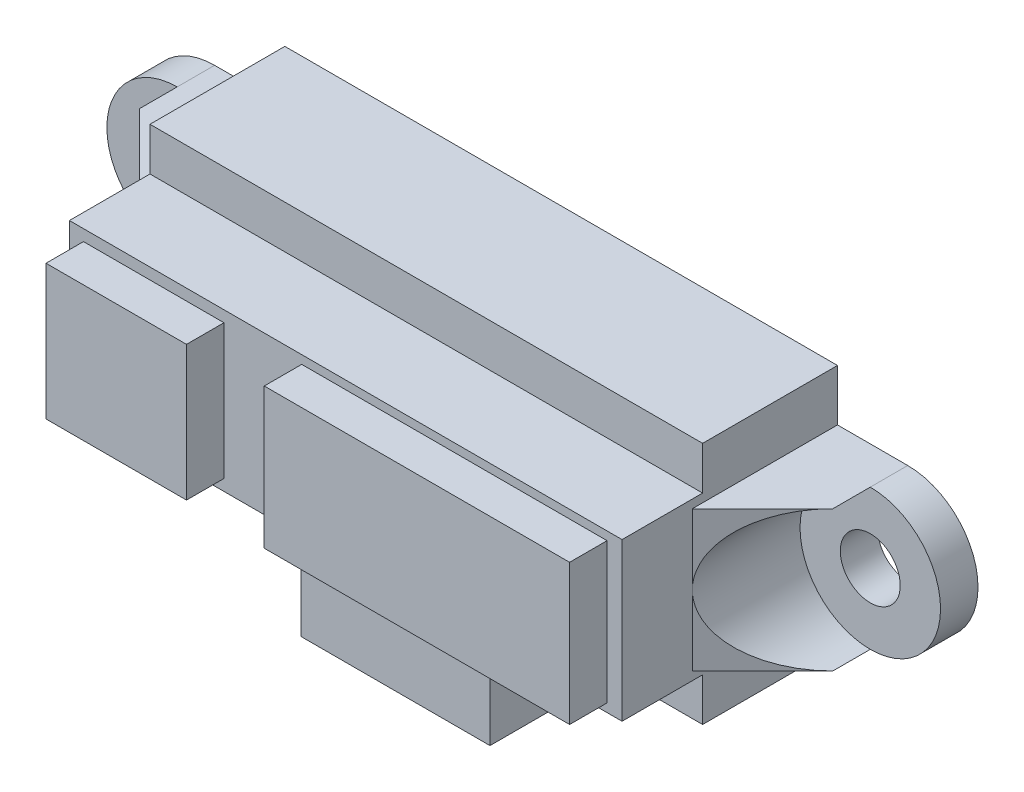
SolidWorks part; units mm, degrees
ref_plane "Front Plane" through (0, 0, 0) normal (0, 0, 1) x (1, 0, 0)
ref_plane "Top Plane" through (0, 0, 0) normal (0, 1, 0) x (1, 0, 0)
ref_plane "Right Plane" through (0, 0, 0) normal (1, 0, 0) x (0, 0, -1)
sketch "Sketch1" plane through (0, 0, 0) normal (0, 0, 1) x (1, 0, 0)
  line L1 (-14.75, 4.2) -> (14.75, 4.2)
  line L2 (-14.75, 4.2) -> (-14.75, -4.2)
  line L3 (-14.75, -4.2) -> (14.75, -4.2)
  line L4 (14.75, 4.2) -> (14.75, -4.2)
  line L5 (0, -4.2) -> (0, 4.2) construction
  line L6 (-14.75, 0) -> (14.75, 0) construction
  point P0 (0, 0)
  dimension "D1" = 29.5
  dimension "D2" = 8.4
extrude "Boss-Extrude1" add sketch "Sketch1" along normal blind 11.5
sketch "Sketch2" plane through (0, 0, 11.5) normal (0, 0, 1) x (1, 0, 0)
  line L0 (-14.75, 4.2) -> (-14.75, -4.2) construction
  line L1 (-14, 3.6) -> (-6.5, 3.6)
  line L2 (-14, 3.6) -> (-14, -3.6)
  line L3 (-14, -3.6) -> (-6.5, -3.6)
  line L4 (-6.5, 3.6) -> (-6.5, -3.6)
  line L5 (-10.25, -3.6) -> (-10.25, 3.6) construction
  line L6 (-14, 0) -> (-6.5, 0) construction
  line L8 (-2.35, 3.75) -> (13.95, 3.75)
  line L9 (-2.35, 3.75) -> (-2.35, -3.75)
  line L10 (-2.35, -3.75) -> (13.95, -3.75)
  line L11 (13.95, 3.75) -> (13.95, -3.75)
  line L12 (5.8, -3.75) -> (5.8, 3.75) construction
  line L13 (-2.35, 0) -> (13.95, 0) construction
  point P0 (-10.25, 0)
  point P6 (5.8, 0)
  dimension "D1" = 4.5
  dimension "D2" = 3.75
  dimension "D3" = 7.2
  dimension "D4" = 16.3
  dimension "D5" = 3.75
  dimension "4.15" = 4.15
extrude "Boss-Extrude2" add sketch "Sketch2" along normal blind 2
sketch "Sketch3" plane through (0, 0, 0) normal (0, 0, 1) x (1, 0, 0)
  line L0 (-14.75, 4.2) -> (-14.75, -4.2) construction
  line L1 (14.75, -6.5) -> (-14.75, -6.5)
  line L2 (14.75, -6.5) -> (14.75, 6.5)
  line L3 (14.75, 6.5) -> (-14.75, 6.5)
  line L4 (-14.75, -6.5) -> (-14.75, 6.5)
  line L5 (0, 6.5) -> (0, -6.5) construction
  line L6 (14.75, 0) -> (-14.75, 0) construction
  point P0 (0, 0)
  dimension "D1" = 13
extrude "Boss-Extrude3" add sketch "Sketch3" along normal offset from surface (7.2 mm away) 6.3 up to face at (-10.25, 0, 13.5)
sketch "Sketch4" plane through (0, 0, 0) normal (1, 0, 0) x (0, 0, -1)
  line L0 (-5.55, -6.5) -> (-5.55, -11.5)
  line L1 (-7.2, -6.5) -> (0, -6.5) construction
  line L2 (-5.55, -11.5) -> (-8.85, -11.5)
  line L3 (-8.85, -11.5) -> (-8.85, -6.5)
  line L4 (-8.85, -6.5) -> (-8.35, -6.5)
  line L5 (-8.35, -6.5) -> (-7.2, -5.35)
  line L6 (-7.2, -6.5) -> (-7.2, -4.2) construction
  line L7 (-7.2, -5.35) -> (-7.2, -6.5)
  line L8 (-7.2, -6.5) -> (-5.55, -6.5)
  dimension "D1" = 3.3
  dimension "D2" = 45
  dimension "D3" = 5
  dimension "D4" = 0.5
extrude "Boss-Extrude4" add sketch "Sketch4" along normal mid plane 10.1
sketch "Sketch5" plane through (0, 0, 0) normal (0, 0, 1) x (1, 0, 0)
  line L0 (-18.5, 3.75) -> (-14.75, 3.75)
  line L1 (-14.75, 4.2) -> (-14.75, -4.2) construction
  line L2 (-18.5, -3.75) -> (-14.75, -3.75)
  line L3 (-14.75, -3.75) -> (-14.75, 3.75)
  line L4 (18.5, 3.75) -> (14.75, 3.75)
  line L5 (14.75, -4.2) -> (14.75, 4.2) construction
  line L6 (18.5, -3.75) -> (14.75, -3.75)
  line L7 (14.75, -3.75) -> (14.75, 3.75)
  arc A0 (-18.5, 3.75) -> (-18.5, -3.75) centre (-18.5, 0) ccw
  arc A1 (18.5, -3.75) -> (18.5, 3.75) centre (18.5, 0) ccw
  circle A2 centre (-18.5, 0) radius 1.6
  circle A3 centre (18.5, 0) radius 1.6
  dimension "D1" = 3.75
  dimension "D2" = 3.2
  dimension "D3" = 37
extrude "Boss-Extrude5" add sketch "Sketch5" along normal blind 10
sketch "Sketch8" plane through (0, 0, 10) normal (0, 0, 1) x (1, 0, 0)
  circle A0 centre (-18.5, 0) radius 3.75
  arc A1 (-18.5, 3.75) -> (-18.5, -3.75) centre (-18.5, 0) ccw construction
  circle A2 centre (18.5, 0) radius 3.75
  arc A3 (18.5, -3.75) -> (18.5, 3.75) centre (18.5, 0) ccw construction
extrude "Cut-Extrude1" cut sketch "Sketch8" against normal offset from surface (8 mm away) 2 up to face at (0, 0, 0)
sketch "Sketch9" plane through (0, 0, 0) normal (0, 1, 0) x (1, 0, 0)
  line L0 (-18.5, -10) -> (-18.5, -2) construction
  line L1 (-18.5, -4) -> (-14.75, -7.75)
  line L2 (-14.75, -10) -> (-14.75, 0) construction
  line L3 (-14.75, -7.75) -> (-14.75, -10)
  line L4 (-14.75, -10) -> (-18.5, -10)
  line L5 (-18.5, -10) -> (-18.5, -4)
  line L6 (-22.25, -2) -> (-18.5, -2) construction
  line L7 (0, 0) -> (0, -16.9734) construction
  line L8 (18.5, -10) -> (18.5, -4)
  line L9 (14.75, -10) -> (18.5, -10)
  line L10 (14.75, -7.75) -> (14.75, -10)
  line L11 (18.5, -4) -> (14.75, -7.75)
  dimension "D1" = 45
  dimension "D2" = 2
extrude "Cut-Extrude2" cut sketch "Sketch9" against normal through all both and the other way through all
